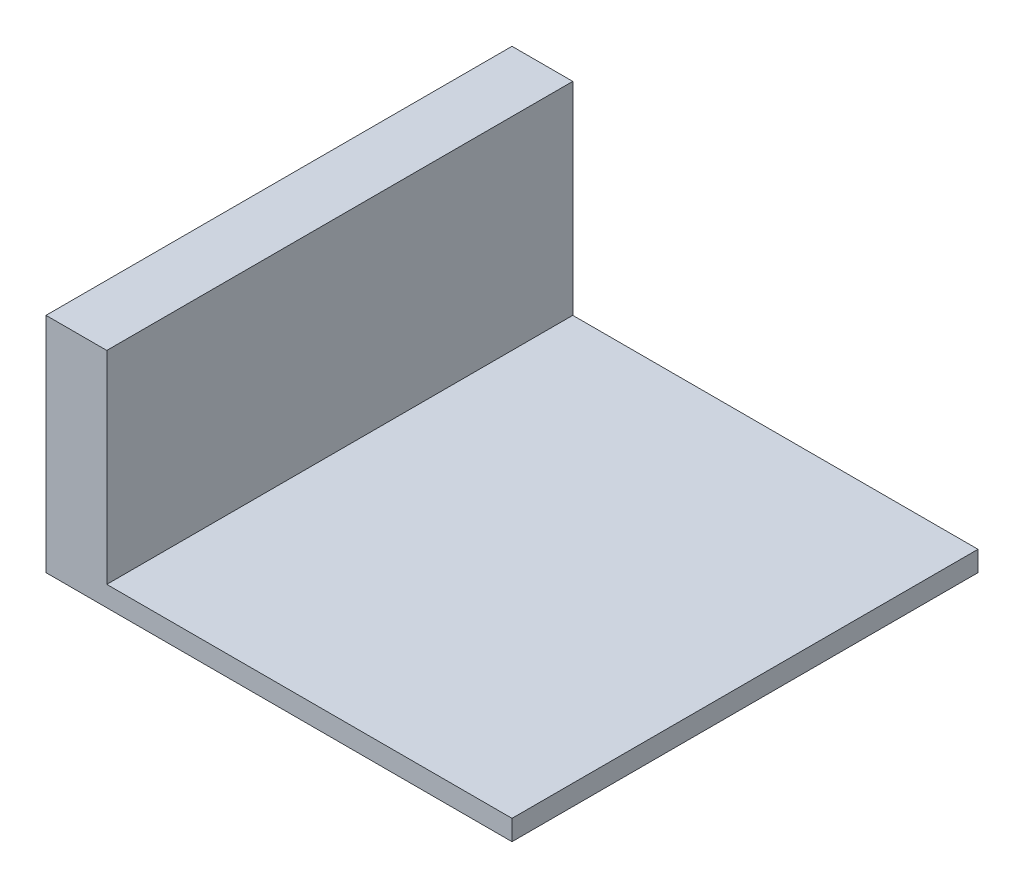
SolidWorks part; units mm, degrees
ref_plane "Front Plane" through (0, 0, 0) normal (0, 0, 1) x (1, 0, 0)
ref_plane "Top Plane" through (0, 0, 0) normal (0, 1, 0) x (1, 0, 0)
ref_plane "Right Plane" through (0, 0, 0) normal (1, 0, 0) x (0, 0, -1)
sketch "Sketch1" plane through (0, 0, 0) normal (0, 1, 0) x (1, 0, 0)
  line L0 (-36.4899, 17.7501) -> (-36.4899, -2.2499)
  line L4 (-33.4899, 0.7501) -> (-33.4899, 20.7501)
  line L5 (-33.4899, 20.7501) -> (-36.4899, 20.7501)
  line L6 (-36.4899, 20.7501) -> (-36.4899, 17.7501)
  line L7 (-33.4899, 0.7501) -> (-33.4899, -2.2499)
  line L8 (-36.4899, -2.2499) -> (-33.4899, -2.2499)
  dimension "D1" = 20
  dimension "D5" = 20
extrude "Boss-Extrude1" add sketch "Sketch1" along normal blind 10
sketch "Sketch2" plane through (0, 0, 0) normal (0, -1, 0) x (1, 0, 0)
  line L1 (-36.4899, 2.2499) -> (-13.4899, 2.2499)
  line L2 (-36.4899, 2.2499) -> (-36.4899, -20.7501)
  line L3 (-36.4899, -20.7501) -> (-13.4899, -20.7501)
  line L4 (-13.4899, 2.2499) -> (-13.4899, -20.7501)
  dimension "D1" = 23
extrude "Boss-Extrude2" add sketch "Sketch2" along normal blind 1
